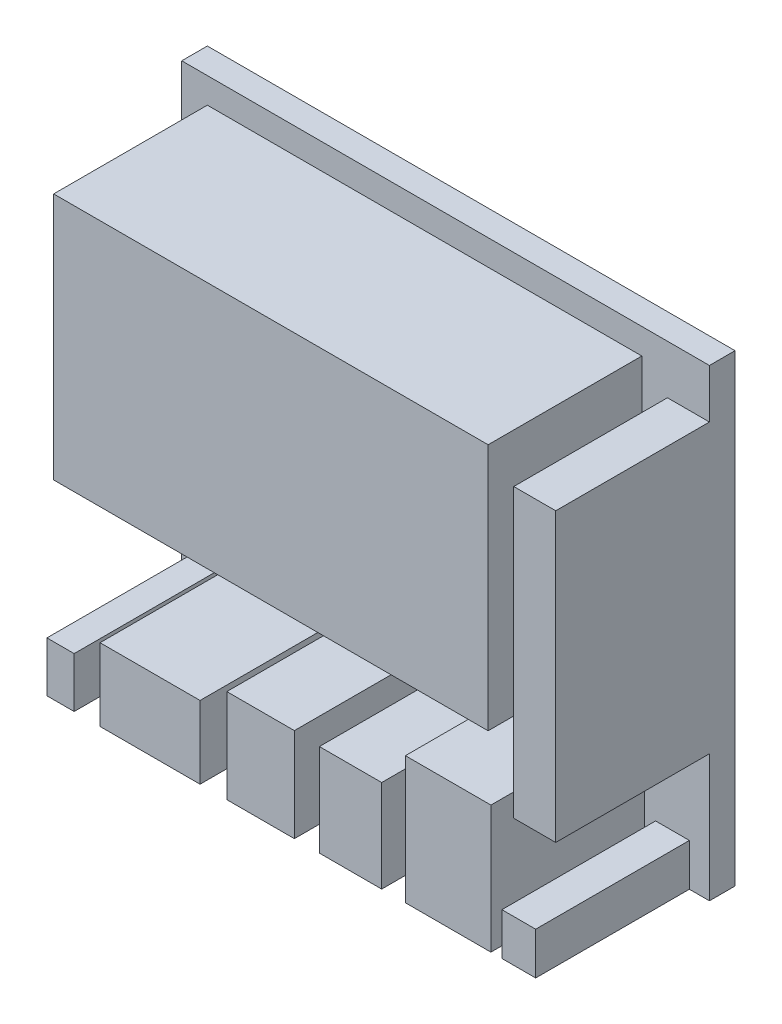
SolidWorks part; units mm, degrees
ref_plane "前视基准面" through (0, 0, 0) normal (0, 0, 1) x (1, 0, 0)
ref_plane "上视基准面" through (0, 0, 0) normal (0, 1, 0) x (1, 0, 0)
ref_plane "右视基准面" through (0, 0, 0) normal (1, 0, 0) x (0, 0, -1)
other "Configuration Table"
sketch "草图1" plane through (0, 0, 0) normal (0, 0, 1) x (1, 0, 0)
  line L1 (0, 0) -> (103, 0)
  line L2 (0, 0) -> (0, 90.5)
  line L3 (0, 90.5) -> (103, 90.5)
  line L4 (103, 0) -> (103, 90.5)
  dimension "D1" = 103
  dimension "D2" = 90.5
extrude "凸台-拉伸1" add sketch "草图1" along normal blind 35
sketch "草图2" plane through (0, 0, 35) normal (0, 0, 1) x (1, 0, 0)
  line L0 (0, 32.1447) -> (0, 0)
  line L1 (0, 0) -> (3.6916, 0)
  line L2 (0, 0) -> (103, 0) construction
  line L3 (3.6916, 0) -> (3.6916, 9.7948)
  line L4 (3.6916, 9.7948) -> (9.0008, 9.7948)
  line L5 (9.0008, 9.7948) -> (9.0008, 0)
  line L6 (9.0008, 0) -> (14.0531, 0)
  line L7 (14.0531, 0) -> (14.0531, 14.162)
  line L8 (14.0531, 14.162) -> (33.5771, 14.162)
  line L9 (33.5771, 14.162) -> (33.5771, 0)
  line L10 (33.5771, 0) -> (38.8007, 0)
  line L11 (38.8007, 0) -> (38.8007, 18.2724)
  line L12 (38.8007, 18.2724) -> (51.988, 18.2724)
  line L13 (51.988, 18.2724) -> (51.988, 0)
  line L14 (51.988, 0) -> (56.869, 0)
  line L15 (56.869, 0) -> (56.869, 18.0155)
  line L16 (56.869, 18.0155) -> (69.0288, 18.0155)
  line L17 (69.0288, 18.0155) -> (69.0288, 0)
  line L18 (69.0288, 0) -> (73.6529, 0)
  line L19 (73.6529, 0) -> (73.6529, 24.866)
  line L20 (73.6529, 24.866) -> (90.3511, 24.866)
  line L21 (90.3511, 24.866) -> (90.3511, 0)
  line L22 (90.3511, 0) -> (92.4919, 0)
  line L23 (92.4919, 0) -> (92.4919, 8.2534)
  line L24 (92.4919, 8.2534) -> (99.0856, 8.2534)
  line L25 (99.0856, 8.2534) -> (99.0856, 0)
  line L26 (99.0856, 0) -> (103, 0)
  line L27 (103, 0) -> (103, 24.866)
  line L28 (103, 0) -> (103, 90.5) construction
  line L29 (103, 24.866) -> (94.804, 24.866)
  line L30 (94.804, 24.866) -> (94.804, 32.1447)
  line L37 (94.804, 32.1447) -> (0, 32.1447)
extrude "切除-拉伸1" cut sketch "草图2" against normal blind 30
sketch "草图3" plane through (0, 0, 35) normal (0, 0, 1) x (1, 0, 0)
  line L0 (0, 90.5) -> (0, 32.1447)
  line L1 (0, 32.1447) -> (94.804, 32.1447)
  line L2 (94.804, 32.1447) -> (94.804, 80.9397)
  line L3 (94.804, 80.9397) -> (103, 80.9397)
  line L4 (103, 24.866) -> (103, 90.5) construction
  line L5 (103, 80.9397) -> (103, 90.5)
  line L6 (103, 90.5) -> (0, 90.5)
  line L7 (89.804, 85.5) -> (5, 85.5)
  line L8 (5, 85.5) -> (5, 37.1447)
  line L9 (5, 37.1447) -> (89.804, 37.1447)
  line L10 (89.804, 37.1447) -> (89.804, 85.5)
  line L11 (89.804, 85.5) -> (89.804, 85.5)
  line L12 (89.804, 85.5) -> (89.804, 85.5)
  dimension "D1" = 5
extrude "切除-拉伸2" cut sketch "草图3" against normal blind 30
